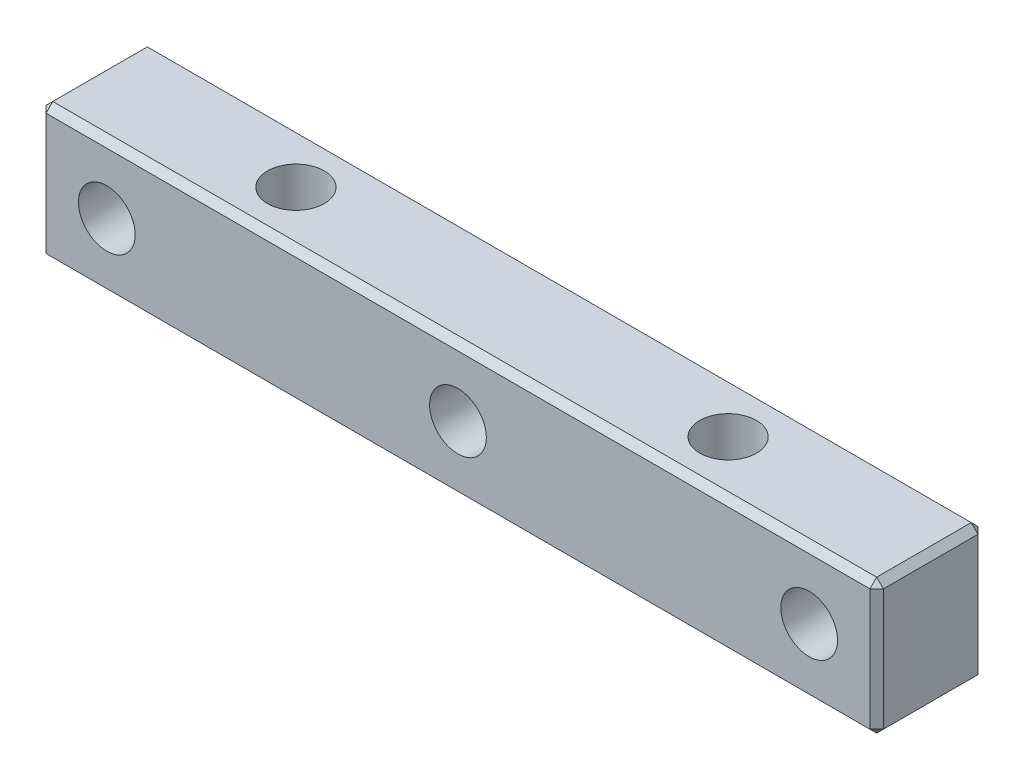
SolidWorks part; units mm, degrees
material "6061 合金"
ref_plane "前视基准面" through (0, 0, 0) normal (0, 0, 1) x (1, 0, 0)
ref_plane "上视基准面" through (0, 0, 0) normal (0, 1, 0) x (1, 0, 0)
ref_plane "右视基准面" through (0, 0, 0) normal (1, 0, 0) x (0, 0, -1)
sketch "草图2" plane through (0, 0, 0) normal (0, 0, 1) x (1, 0, 0)
  line L10 (31, 5) -> (31, -5)
  line L11 (26, 0) -> (-26, 0) construction
  line L41 (31, -5) -> (-31, -5)
  line L48 (-31, 5) -> (31, 5)
  line L49 (-31, 5) -> (-31, -5)
  circle A3 centre (-26, 0) radius 0.5
  circle A5 centre (26, 0) radius 0.5
  dimension "D1" = 52
  dimension "D2" = 1
  dimension "D3" = 5
  dimension "D4" = 5
  dimension "D7" = 5
  dimension "D6" = 5
extrude "凸台-拉伸1" add sketch "草图2" along normal mid plane 8
hole_wizard "M5 螺纹孔1" positions "草图5" profile "草图4" tap size "M5" standard "GB" end condition through all
sketch "草图5" plane through (0, 0, 4) normal (0, 0, 1) x (1, 0, 0)
  point P0 (0, 0)
  point P3 (-26, 0)
  point P6 (26, 0)
sketch "草图4" plane through (0, 0, 4) normal (1, 0, 0) x (0, -1, 0)
  line L0 (0, 0) -> (0, 8)
  line L1 (0, 8) -> (2.1, 8)
  line L2 (2.1, 8) -> (2.1, 0)
  line L5 (2.1, 0) -> (0, 0)
  line L11 (0, -6.35) -> (0, 107.95) construction
  dimension "通孔螺纹孔钻头直径" = 4.2
  dimension "通孔螺纹孔钻头深度" = 8
cosmetic thread "孔螺蚊线3" parameters "D2"=5
cosmetic thread "孔螺蚊线4" parameters "D2"=5
cosmetic thread "孔螺蚊线7" parameters "D2"=5
hole_wizard "M5 螺纹孔2" positions "草图6" profile "草图7" tap size "M5" standard "GB" end condition through all
sketch "草图6" plane through (0, 5, 0) normal (0, 1, 0) x (1, 0, 0)
  line L1 (-16, 0) -> (16, 0) construction
  line L2 (-31, -4) -> (-31, 4) construction
  point P0 (16, 0)
  point P2 (-16, 0)
  dimension "D1" = 15
sketch "草图7" plane through (16, 5, 0) normal (1, 0, 0) x (0, 0, 1)
  line L0 (0, 0) -> (0, 10)
  line L1 (0, 10) -> (2.1, 10)
  line L2 (2.1, 10) -> (2.1, 0)
  line L5 (2.1, 0) -> (0, 0)
  line L11 (0, -6.35) -> (0, 107.95) construction
  dimension "通孔螺纹孔钻头直径" = 4.2
  dimension "通孔螺纹孔钻头深度" = 10
cosmetic thread "孔螺蚊线5" parameters "D2"=5
cosmetic thread "孔螺蚊线6" parameters "D2"=5
chamfer "倒角1" distance 0.5 angle 45 12 edges at (0, -5, -4) (0, -5, 4) (-31, 0, -4) (-31, 0, 4) (31, -5, 0) (31, 0, 4) (31, 0, -4) (0, 5, -4) (31, 5, 0) (0, 5, 4) (-31, 5, 0) (-31, -5, 0)
